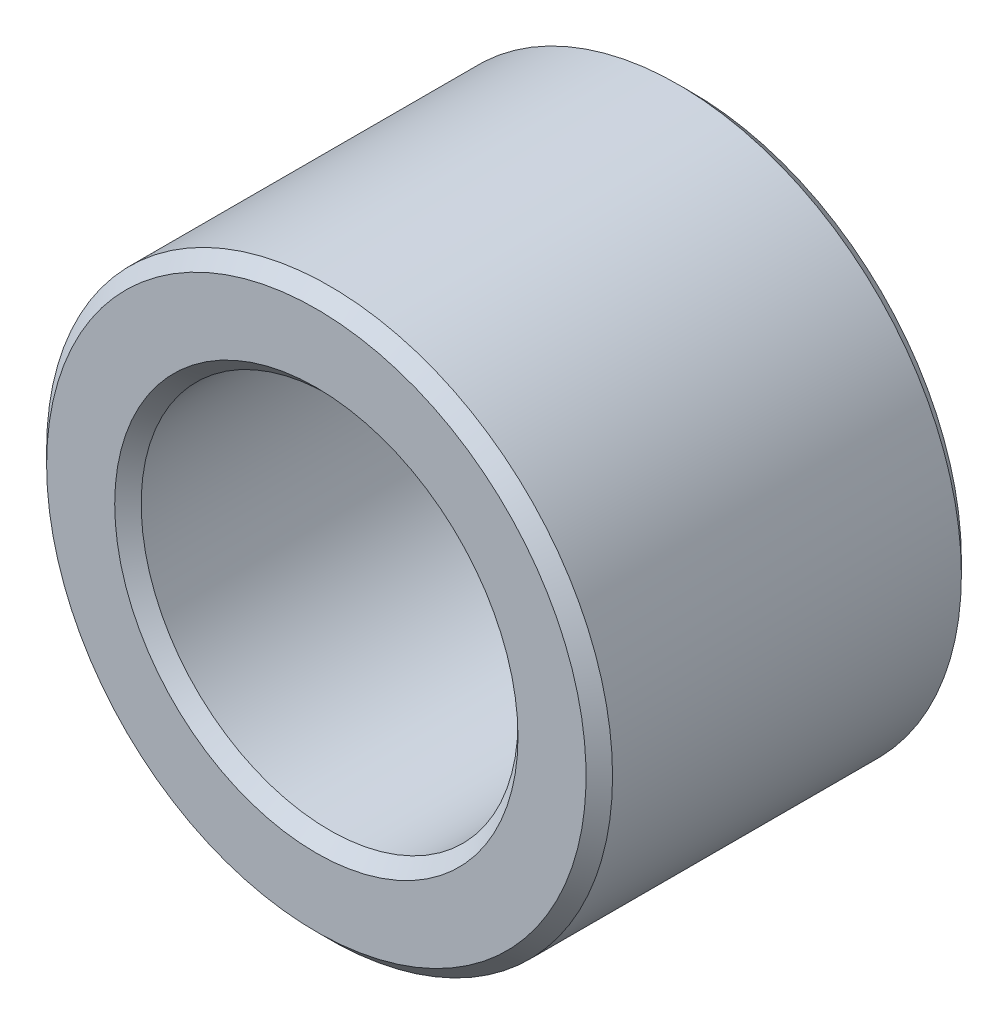
SolidWorks part; units mm, degrees
ref_plane "Front Plane" through (0, 0, 0) normal (0, 0, 1) x (1, 0, 0)
ref_plane "Top Plane" through (0, 0, 0) normal (0, 1, 0) x (1, 0, 0)
ref_plane "Right Plane" through (0, 0, 0) normal (1, 0, 0) x (0, 0, -1)
sketch "Sketch1" plane through (0, 0, 0) normal (0, 0, 1) x (1, 0, 0)
  line L0 (3.1877, 0) -> (4.7879, 0) construction
  circle A0 centre (0, 0) radius 3.1877 construction
  circle A1 centre (0, 0) radius 4.7879 construction
  circle A2 centre (0, 0) radius 4.7625 construction
  circle A3 centre (0, 0) radius 3.175 construction
  dimension "For Shaft Diameter" = 6.35
  dimension "For Housing ID" = 9.525
  dimension "OD" = 9.5758
  dimension "ID" = 6.3754
  dimension "D3" = 1.6002
sketch "Sketch13" plane through (0, 0, 0) normal (1, 0, 0) x (0, 0, -1)
  line L0 (3.175, 0) -> (-3.175, 0) construction
  line L1 (3.175, 4.7879) -> (-3.175, 4.7879) construction
  line L2 (0, 4.7879) -> (0, -4.7879) construction
  line L3 (0, 4.7879) -> (0, -4.7879) construction
  point P4 (0, 0)
  point P8 (0, 4.7879)
  dimension "Length" = 6.35
sketch "Sketch14" plane through (0, 0, 0) normal (0, 0, 1) x (1, 0, 0)
  circle A0 centre (0, 0) radius 3.1877 construction
  circle A1 centre (0, 0) radius 4.7879 construction
  circle A2 centre (0, 0) radius 3.1877
  circle A3 centre (0, 0) radius 4.7879
extrude "Boss-Extrude1" add sketch "Sketch14" against normal up to vertex (3.175 mm away) and the other way up to vertex (3.175 mm away) up to point (0, 4.7879, -3.175) other way up to point (0, 4.7879, 3.175)
chamfer "Chamfer1" distance 0.224 angle 45 4 edges at (4.7879, 0, -3.175) (3.1877, 0, -3.175) (3.1877, 0, 3.175) (4.7879, 0, 3.175)
equation "\"D1@Chamfer1\"=(\"OD@Sketch1\"-\"ID@Sketch1\")*.07"
